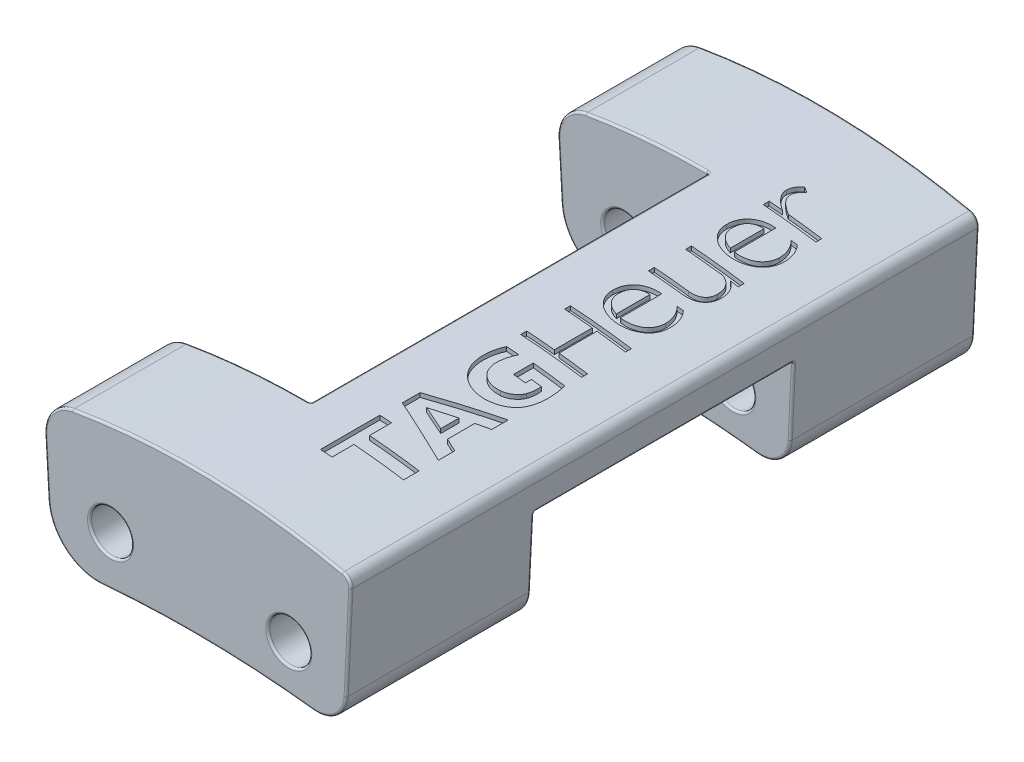
SolidWorks part; units mm, degrees
ref_plane "Front Plane" through (0, 0, 0) normal (0, 0, 1) x (1, 0, 0)
ref_plane "Top Plane" through (0, 0, 0) normal (0, 1, 0) x (1, 0, 0)
ref_plane "Right Plane" through (0, 0, 0) normal (1, 0, 0) x (0, 0, -1)
sketch "Sketch1" plane through (0, 0, 0) normal (0, 0, 1) x (1, 0, 0)
  line L0 (3.2145, 1.1802) -> (3.1395, -0.1311)
  line L1 (-3.7507, -0.1311) -> (-3.8257, 1.1802)
  arc A0 (-3.1613, 2.0145) -> (-3.8257, 1.1802) centre (-3.027, 1.2258) ccw
  arc A1 (2.5502, 2.0145) -> (-3.1613, 2.0145) centre (-0.3056, -14.744) ccw
  arc A2 (3.2145, 1.1802) -> (2.5502, 2.0145) centre (2.4158, 1.2258) ccw
  arc A3 (-3.7507, -0.1311) -> (-2.4498, -1.2582) centre (-2.5527, -0.0627) ccw
  arc A4 (1.8386, -1.2582) -> (-2.4498, -1.2582) centre (-0.3056, -26.1661) ccw
  arc A5 (1.8386, -1.2582) -> (3.1395, -0.1311) centre (1.9415, -0.0627) ccw
  circle A6 centre (-2.2556, -0.0709) radius 0.5
extrude "Boss-Extrude1" add sketch "Sketch1" along normal mid plane 15
sketch "Sketch2" plane through (0, 0, 7.5) normal (0, 0, 1) x (1, 0, 0)
  line L0 (1.8386, -1.2582) -> (2.0484, 3.0041)
  line L1 (2.0484, 3.0041) -> (6.0439, 1.739)
  line L2 (6.0439, 1.739) -> (3.826, -1.9442)
  line L3 (3.826, -1.9442) -> (1.8386, -1.2582)
extrude "Cut-Extrude1" cut sketch "Sketch2" against normal blind 15
sketch "Sketch3" plane through (0, 0, 0) normal (0, 1, 0) x (1, 0, 0)
  line L0 (-2.7216, 0) -> (2.7216, 0) construction
  line L1 (-6.7347, 4.75) -> (-0.227, 4.75)
  line L2 (-6.7347, 4.75) -> (-6.7347, -4.75)
  line L3 (-6.7347, -4.75) -> (-0.227, -4.75)
  line L4 (-0.227, 4.75) -> (-0.227, -4.75)
  line L5 (-3.827, 7.5) -> (-3.827, -7.5) construction
  dimension "D1" = 9.5
  dimension "D2" = 4.75
  dimension "D3" = 3.6
extrude "Cut-Extrude2" cut sketch "Sketch3" against normal mid plane 10
sketch "Sketch4" plane through (1.8959, -0.0934, 0) normal (0.9988, -0.0492, 0) x (0, 0, -1)
  line L4 (-7.5, 2.1945) -> (-7.5, -1.1663)
  line L5 (-7.5, -1.1663) -> (7.5, -1.1663)
  line L6 (7.5, -1.1663) -> (7.5, 2.1945)
  line L7 (7.5, 2.1945) -> (-7.5, 2.1945)
  line L8 (-7.5, 2.1945) -> (-7.5, -1.1663)
  line L9 (-7.5, -1.1663) -> (7.5, -1.1663)
  line L10 (7.5, -1.1663) -> (7.5, 2.1945)
  line L11 (7.5, 2.1945) -> (-7.5, 2.1945)
  dimension "D1" = 0
extrude "Boss-Extrude2" add sketch "Sketch4" along normal blind 1.5
sketch "Sketch5" plane through (0, 0, 7.5) normal (0, 0, 1) x (1, 0, 0)
  line L4 (1.8386, -1.2582) -> (3.3368, -1.332)
  line L5 (3.3368, -1.332) -> (3.502, 2.0247)
  line L6 (3.502, 2.0247) -> (2.0038, 2.0984)
  line L7 (-3.8257, 1.1802) -> (-3.7507, -0.1311)
  line L9 (3.4923, 1.8264) -> (3.502, 2.0247)
  line L11 (-3.8257, 1.1802) -> (-3.7507, -0.1311)
  arc A4 (1.8386, -1.2582) -> (-2.4498, -1.2582) centre (-0.3056, -26.1661) ccw
  arc A5 (2.0038, 2.0984) -> (-3.1613, 2.0145) centre (-0.3056, -14.744) ccw
  arc A6 (-3.1613, 2.0145) -> (-3.8257, 1.1802) centre (-3.027, 1.2258) ccw
  arc A7 (-3.7507, -0.1311) -> (-2.4498, -1.2582) centre (-2.5527, -0.0627) ccw
  arc A8 (4.8539, -1.7043) -> (-2.4498, -1.2582) centre (-0.3056, -26.1661) ccw
  arc A9 (4.2803, 1.6258) -> (-3.1613, 2.0145) centre (-0.3056, -14.744) ccw
  arc A10 (-3.1613, 2.0145) -> (-3.8257, 1.1802) centre (-3.027, 1.2258) ccw
  arc A11 (-3.7507, -0.1311) -> (-2.4498, -1.2582) centre (-2.5527, -0.0627) ccw
  dimension "D1" = 0
sketch "Sketch6" plane through (0, 0, 7.5) normal (0, 0, 1) x (1, 0, 0)
  line L0 (-3.1613, 2.0145) -> (3.5829, 4.0791)
  line L1 (3.5829, 4.0791) -> (5.2679, 2.2022)
  line L2 (5.2679, 2.2022) -> (4.2803, 1.6258)
  arc A0 (4.2803, 1.6258) -> (-3.1613, 2.0145) centre (-0.3056, -14.744) ccw construction
  arc A1 (4.2803, 1.6258) -> (-3.1613, 2.0145) centre (-0.3056, -14.744) ccw
extrude "Cut-Extrude3" cut sketch "Sketch6" against normal through all
sketch "Sketch7" plane through (0, 0, 7.5) normal (0, 0, 1) x (1, 0, 0)
  line L0 (3.379, -0.4744) -> (3.3368, -1.332)
  line L1 (3.4923, 1.8264) -> (3.3368, -1.332) construction
  line L2 (3.3368, -1.332) -> (3.3318, -1.4322)
  line L3 (3.379, -0.4744) -> (0.7899, -1.1901)
  arc A0 (4.8539, -1.7043) -> (-2.4498, -1.2582) centre (-0.3056, -26.1661) ccw construction
  arc A1 (3.3318, -1.4322) -> (0.7899, -1.1901) centre (-0.3056, -26.1661) ccw
extrude "Boss-Extrude3" add sketch "Sketch7" against normal up to surface (15 mm away)
sketch "Sketch8" plane through (0, 0, 7.5) normal (0, 0, 1) x (1, 0, 0)
  line L0 (4.0256, 0) -> (-4.0256, 0) construction
  line L1 (0, -2.0285) -> (0, 2.0285) construction
  circle A0 centre (2, -0.2) radius 0.5
  dimension "D1" = 1
  dimension "D2" = 0.2
  dimension "D3" = 2
extrude "Cut-Extrude4" cut sketch "Sketch8" against normal through all
fillet "Fillet1" radius 0.25 1 edges at (3.4923, 1.8264, 0)
fillet "Fillet2" radius 0.7 1 edges at (3.3318, -1.4322, 0)
sketch "Sketch9" plane through (0, 0, 0) normal (0, 1, 0) x (1, 0, 0)
  line L0 (-1.9773, 0) -> (1.9773, 0) construction
  line L1 (1.1353, 3.1) -> (8.6305, 3.1)
  line L2 (1.1353, 3.1) -> (1.1353, -3.1)
  line L3 (1.1353, -3.1) -> (8.6305, -3.1)
  line L4 (8.6305, 3.1) -> (8.6305, -3.1)
  dimension "D1" = 6.2
  dimension "D2" = 3.1
extrude "Cut-Extrude5" cut sketch "Sketch9" against normal blind 2 and the other way blind 1
fillet "Fillet3" radius 0.05 51 edges at (1.1353, -1.2077, 0) (3.4516, 1, 0) (3.1225, -1.1731, 3.1) (3.1225, -1.1731, -3.1) (3.1225, -1.1731, -7.5) (3.1225, -1.1731, 7.5) (3.4306, 1.7803, 7.5) (3.4306, 1.7803, -7.5) (-0.227, -1.1662, 0) (0.0715, -1.169, 7.5) (0.0715, -1.169, -7.5) (-3.3384, -0.9696, 4.75) (-3.3384, -0.9696, 7.5) (-3.3384, -0.9696, -4.75) (-3.3384, -0.9696, -7.5) (-3.7882, 0.5245, 4.75) (-3.7882, 0.5245, 7.5) (-3.7882, 0.5245, -4.75) (-3.7882, 0.5245, -7.5) (-3.6528, 1.7242, 4.75) (-3.6528, 1.7242, 7.5) (-3.6528, 1.7242, -4.75) (-3.6528, 1.7242, -7.5) (0.0686, 2.2519, 7.5) (0.0686, 2.2519, -7.5) (-1.7556, -0.0709, 4.75) (-1.7556, -0.0709, 7.5) (-2.7556, -0.0709, -4.75) (-1.7556, -0.0709, -7.5) (-0.227, 2.2559, 0) (-1.6994, 2.1988, -4.75) (-1.3394, -1.1875, -4.75) (-1.6994, 2.1988, 4.75) (-1.3394, -1.1875, 4.75) (-0.227, 0.5448, -4.75) (-0.227, 0.5448, 4.75) (3.4255, 0.4712, -7.5) (3.4255, 0.4712, 7.5) (2.5, -0.2, -7.5) (2.5, -0.2, -3.1) (2.5, -0.2, 7.5) (1.5, -0.2, 3.1) (1.8631, -1.2604, 3.1) (3.4104, 0.1633, 3.1) (1.8631, -1.2604, -3.1) (3.4104, 0.1633, -3.1) (1.1353, -0.1038, 3.1) (1.1353, -0.1038, -3.1) (2.2934, 1, -3.1) (2.2934, 1, 3.1) (1.1353, 1, 0)
sketch "Sketch11" plane through (0, 0, 0) normal (0, 1, 0) x (1, 0, 0)
  line L59 (2.284, -4.6731) -> (1.0996, -4.6731)
  line L60 (1.0996, -4.6731) -> (1.0996, -4.1502)
  line L61 (1.0996, -4.1502) -> (0.8243, -4.1502)
  line L62 (0.8243, -4.1502) -> (0.8243, -5.5673)
  line L63 (0.8243, -5.5673) -> (1.0996, -5.5673)
  line L64 (1.0996, -5.5673) -> (1.0996, -5.0444)
  line L65 (1.0996, -5.0444) -> (2.284, -5.0444)
  line L66 (2.284, -5.0444) -> (2.284, -4.6731)
  line L67 (0.9146, -1.2119) -> (1.203, -1.2119)
  line L68 (2.0345, -1.5079) -> (1.7995, -1.5079)
  line L69 (1.7995, -1.5079) -> (1.8, -1.6521)
  line L70 (1.8, -1.6521) -> (1.5167, -1.6521)
  line L71 (1.5167, -1.6521) -> (1.5167, -1.1796)
  line L72 (1.5167, -1.1796) -> (2.269, -1.1796)
  line L73 (2.269, -1.1796) -> (2.269, -1.1793)
  line L74 (1.6092, 0.2483) -> (2.2882, 0.2478)
  line L75 (2.2882, 0.2478) -> (2.2882, 0.3886)
  line L76 (2.2882, 0.3886) -> (0.8354, 0.3886)
  line L77 (0.8354, 0.3886) -> (0.8354, 0.2478)
  line L78 (0.8354, 0.2478) -> (1.4963, 0.2483)
  line L79 (1.4963, 0.2483) -> (1.4963, -0.6579)
  line L80 (1.4963, -0.6579) -> (0.8354, -0.6576)
  line L81 (0.8354, -0.6576) -> (0.8354, -0.7983)
  line L82 (0.8354, -0.7983) -> (2.2882, -0.7983)
  line L83 (2.2882, -0.7983) -> (2.2882, -0.6576)
  line L84 (2.2882, -0.6576) -> (1.6092, -0.6579)
  line L85 (1.6092, -0.6579) -> (1.6092, 0.2483)
  line L86 (1.8452, 2.1945) -> (1.0299, 2.1945)
  line L87 (1.0299, 2.1945) -> (1.0299, 2.0543)
  line L88 (1.0299, 2.0543) -> (1.8152, 2.0541)
  line L89 (2.0988, 2.9416) -> (2.2873, 2.9411)
  line L90 (2.2873, 2.9411) -> (2.2873, 3.0819)
  line L91 (2.2873, 3.0819) -> (1.0299, 3.0819)
  line L92 (1.0299, 3.0819) -> (1.0299, 2.9416)
  line L93 (1.0299, 2.9416) -> (1.9254, 2.9411)
  line L94 (1.3446, 4.9352) -> (1.0318, 4.9356)
  line L95 (1.0318, 4.9356) -> (1.0318, 4.7949)
  line L96 (1.0318, 4.7949) -> (2.2892, 4.7949)
  line L97 (2.2892, 4.7949) -> (2.2892, 4.9352)
  line L98 (2.2892, 4.9352) -> (1.49, 4.9356)
  line L99 (1.2837, 5.584) -> (1.1545, 5.6593)
  line L100 (2.0068, -3.7189) -> (2.2928, -3.831)
  line L101 (2.2928, -3.831) -> (2.2928, -4.2223)
  line L102 (2.2928, -4.2223) -> (0.8368, -3.6265)
  line L103 (0.8368, -3.6265) -> (0.8368, -3.2021)
  line L104 (0.8368, -3.2021) -> (2.2928, -2.5575)
  line L105 (2.2928, -2.5575) -> (2.2928, -2.9488)
  line L106 (2.2928, -2.9488) -> (2.0068, -3.0682)
  line L107 (2.0068, -3.0682) -> (2.0068, -3.7189)
  line L108 (1.7423, -3.1808) -> (1.198, -3.4072)
  line L109 (1.198, -3.4072) -> (1.7423, -3.6166)
  line L110 (1.7423, -3.6166) -> (1.7423, -3.1808)
  line L111 (2.0023, 1.7704) -> (2.1477, 1.7704)
  line L112 (1.6102, 1.7942) -> (1.6102, 0.8056)
  line L113 (1.4954, 0.8231) -> (1.4954, 1.6287)
  line L114 (2.0023, 4.4917) -> (2.1477, 4.4917)
  line L115 (1.6102, 4.5156) -> (1.6102, 3.527)
  line L116 (1.4954, 3.5446) -> (1.4954, 4.35)
  spline S34 degree 3 poles (2.269, -1.1793) (2.333, -1.4639) (2.3517, -1.8301) (2.2301, -2.0948) knots 0 0 0 0 1 1 1 1
  spline S35 degree 3 poles (2.2301, -2.0948) (2.1311, -2.3205) (1.8952, -2.4597) (1.6645, -2.4885) knots 1 1 1 1 2 2 2 2
  spline S36 degree 3 poles (1.6645, -2.4885) (1.3811, -2.5186) (1.1327, -2.412) (0.9659, -2.185) knots 2 2 2 2 3 3 3 3
  spline S37 degree 3 poles (0.9659, -2.185) (0.7767, -1.9204) (0.7829, -1.5003) (0.9146, -1.2119) knots 3 3 3 3 4 4 4 4
  spline S38 degree 3 poles (1.203, -1.2119) (1.1027, -1.4301) (1.0438, -1.7586) (1.203, -1.9681) knots 7 7 7 7 8 8 8 8
  spline S39 degree 3 poles (1.203, -1.9681) (1.3184, -2.1185) (1.5014, -2.165) (1.6845, -2.1274) knots 8 8 8 8 9 9 9 9
  spline S40 degree 3 poles (1.6845, -2.1274) (1.8288, -2.0972) (1.9592, -1.9731) (2.0068, -1.8352) knots 9 9 9 9 10 10 10 10
  spline S41 degree 3 poles (2.0068, -1.8352) (2.0382, -1.7373) (2.0483, -1.617) (2.0345, -1.5079) knots 10 10 10 10 11 11 11 11
  spline S42 degree 2 poles (1.9254, 2.9411) (2.2043, 2.8445) (2.2043, 2.531) knots 0 0 0 1 1 1
  spline S43 degree 3 poles (2.2043, 2.531) (2.2043, 2.276) (2.0255, 2.1945) (1.8452, 2.1945) knots 1 1 1 1 2 2 2 2
  spline S44 degree 3 poles (1.8152, 2.0541) (2.2907, 2.0541) (2.3172, 2.4103) (2.3172, 2.509) knots 7 7 7 7 8 8 8 8
  spline S45 degree 2 poles (2.3172, 2.509) (2.3172, 2.8084) (2.0988, 2.9416) knots 8 8 8 9 9 9
  spline S46 degree 2 poles (1.1545, 5.6593) (1.0097, 5.5309) (1.0097, 5.3703) knots 0 0 0 1 1 1
  spline S47 degree 2 poles (1.0097, 5.3703) (1.0097, 5.1553) (1.3446, 4.9352) knots 1 1 1 2 2 2
  spline S48 degree 2 poles (1.49, 4.9356) (1.144, 5.1349) (1.144, 5.3253) knots 9 9 9 10 10 10
  spline S49 degree 2 poles (1.144, 5.3253) (1.144, 5.456) (1.2837, 5.584) knots 10 10 10 11 11 11
  spline S50 degree 3 poles (1.6102, 0.8056) (1.6247, 0.8047) (1.6386, 0.8043) (1.6533, 0.8043) knots 0 0 0 0 1 1 1 1
  spline S51 degree 3 poles (1.6533, 0.8043) (1.9606, 0.8043) (2.1902, 1.0062) (2.1902, 1.3051) knots 1 1 1 1 2 2 2 2
  spline S52 degree 2 poles (2.1902, 1.3051) (2.1902, 1.5748) (2.0023, 1.7704) knots 2 2 2 3 3 3
  spline S53 degree 2 poles (2.1477, 1.7704) (2.3148, 1.5888) (2.3148, 1.2894) knots 6 6 6 7 7 7
  spline S54 degree 3 poles (2.3148, 1.2894) (2.3148, 0.8347) (1.9277, 0.6553) (1.6549, 0.6553) knots 7 7 7 7 8 8 8 8
  spline S55 degree 3 poles (1.6549, 0.6553) (1.2986, 0.6553) (1.0046, 0.8868) (1.0046, 1.2233) knots 8 8 8 8 9 9 9 9
  spline S56 degree 3 poles (1.0046, 1.2233) (1.0046, 1.6037) (1.2999, 1.7942) (1.6102, 1.7942) knots 9 9 9 9 10 10 10 10
  spline S57 degree 2 poles (1.4954, 1.6287) (1.1328, 1.6022) (1.1328, 1.2226) knots 2 2 2 3 3 3
  spline S58 degree 3 poles (1.1328, 1.2226) (1.1328, 1.0082) (1.2921, 0.8699) (1.4954, 0.8231) knots 3 3 3 3 4 4 4 4
  spline S59 degree 3 poles (1.6102, 3.527) (1.6247, 3.5261) (1.6386, 3.5256) (1.6533, 3.5256) knots 0 0 0 0 1 1 1 1
  spline S60 degree 3 poles (1.6533, 3.5256) (1.9606, 3.5256) (2.1902, 3.7275) (2.1902, 4.0265) knots 1 1 1 1 2 2 2 2
  spline S61 degree 2 poles (2.1902, 4.0265) (2.1902, 4.2961) (2.0023, 4.4917) knots 2 2 2 3 3 3
  spline S62 degree 2 poles (2.1477, 4.4917) (2.3148, 4.3103) (2.3148, 4.0108) knots 6 6 6 7 7 7
  spline S63 degree 3 poles (2.3148, 4.0108) (2.3148, 3.5562) (1.9277, 3.3766) (1.6549, 3.3766) knots 7 7 7 7 8 8 8 8
  spline S64 degree 3 poles (1.6549, 3.3766) (1.2986, 3.3766) (1.0046, 3.6082) (1.0046, 3.9447) knots 8 8 8 8 9 9 9 9
  spline S65 degree 3 poles (1.0046, 3.9447) (1.0046, 4.3251) (1.2999, 4.5156) (1.6102, 4.5156) knots 9 9 9 9 10 10 10 10
  spline S66 degree 2 poles (1.4954, 4.35) (1.1328, 4.3236) (1.1328, 3.9439) knots 2 2 2 3 3 3
  spline S67 degree 3 poles (1.1328, 3.9439) (1.1328, 3.7296) (1.2921, 3.5913) (1.4954, 3.5446) knots 3 3 3 3 4 4 4 4
extrude "Cut-Extrude6" cut sketch "Sketch11" against normal offset from surface (8.0412 mm away) 0.1 from offset 10
